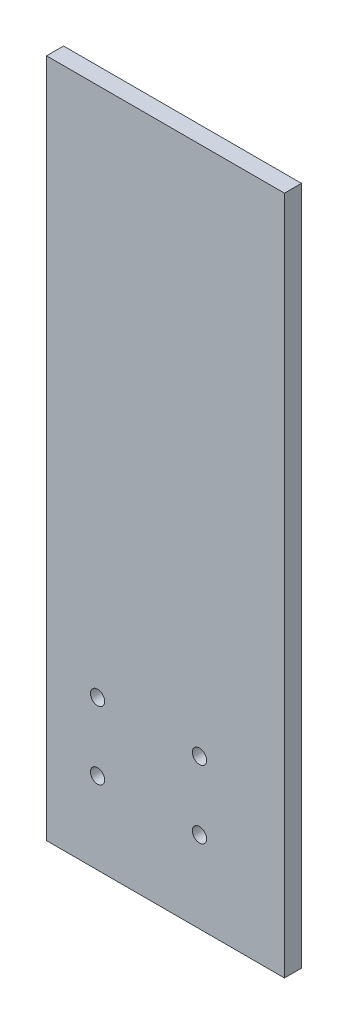
SolidWorks part; units mm, degrees
ref_plane "정면" through (0, 0, 0) normal (0, 0, 1) x (1, 0, 0)
ref_plane "윗면" through (0, 0, 0) normal (0, 1, 0) x (1, 0, 0)
ref_plane "우측면" through (0, 0, 0) normal (1, 0, 0) x (0, 0, -1)
sketch "스케치1" plane through (0, 0, 0) normal (0, 0, 1) x (1, 0, 0)
  line L1 (-50, 100) -> (50, 100)
  line L2 (-50, 100) -> (-50, -100)
  line L3 (-50, -100) -> (50, -100)
  line L4 (50, 100) -> (50, -100)
  line L5 (-50, 100) -> (50, -100) construction
  line L6 (-50, -100) -> (50, 100) construction
  point P0 (0, 0)
  dimension "D1" = 100
  dimension "D2" = 200
extrude "보스-돌출1" add sketch "스케치1" along normal blind 5
sketch "스케치3" plane through (0, 0, 0) normal (0, 0, -1) x (-1, 0, 0)
  text T0 "front"
extrude "컷-돌출2" cut sketch "스케치3" against normal blind 0.001
ref_plane "평면1" through (0, 0, -5) normal (0, 0, -1) x (-1, 0, 0)
hole_wizard "M4x0.7 Helicoil용 탭 구멍1" positions "스케치10" profile "스케치11" tap size "M4x0.7" standard "Helicoil® Metric" end condition through all
sketch "스케치10" plane through (0, 0, -5) normal (0, 0, -1) x (-1, 0, 0)
  line L0 (50, -100) -> (-50, -100) construction
  line L1 (-50, -100) -> (-50, 100) construction
  line L2 (50, 100) -> (50, -100) construction
  point P0 (-5, -76)
  point P2 (25, -76)
  point P4 (-5, -56)
  point P6 (25, -56)
  dimension "D1" = 24
  dimension "D2" = 24
  dimension "D3" = 45
  dimension "D4" = 25
  dimension "D5" = 25
  dimension "D6" = 45
  dimension "D7" = 20
  dimension "D8" = 20
sketch "스케치11" plane through (5, -76, -5) normal (1, 0, 0) x (0, 1, 0)
  line L0 (0, 0) -> (0, 10)
  line L1 (0, 10) -> (2.1, 10)
  line L2 (2.1, 10) -> (2.1, 0)
  line L5 (2.1, 0) -> (0, 0)
  line L11 (0, -6.35) -> (0, 107.95) construction
  dimension "관통 탭 드릴 지름" = 4.2
  dimension "관통 탭 드릴 깊이" = 10
cosmetic thread "구멍 나사산1" parameters "D1"=4.7, "D2"=5.007
cosmetic thread "구멍 나사산2" parameters "D1"=4.7, "D2"=5.007
cosmetic thread "구멍 나사산3" parameters "D1"=4.7, "D2"=5.007
cosmetic thread "구멍 나사산4" parameters "D1"=4.7, "D2"=5.007
sketch "스케치13" plane through (0, 0, 5) normal (0, 0, 1) x (1, 0, 0)
  line L0 (-50, -100) -> (50, -100) construction
  line L1 (50, 100) -> (40, 100)
  line L2 (50, 100) -> (50, -100)
  line L3 (50, -100) -> (40, -100)
  line L4 (40, 100) -> (40, -100)
  line L5 (0, -2.75) -> (0, 2.75) construction
  line L6 (-40, 100) -> (-40, -100)
  line L7 (-50, -100) -> (-40, -100)
  line L8 (-50, 100) -> (-50, -100)
  line L9 (-50, 100) -> (-40, 100)
  dimension "D1" = 10
extrude "컷-돌출4" cut sketch "스케치13" against normal blind 10
sketch "스케치14" plane through (0, 0, 5) normal (0, 0, 1) x (1, 0, 0)
  line L0 (-40, -100) -> (40, -100) construction
  line L1 (40, 100) -> (30, 100)
  line L2 (40, 100) -> (40, -100)
  line L3 (40, -100) -> (30, -100)
  line L4 (30, 100) -> (30, -100)
  dimension "D1" = 10
extrude "컷-돌출5" cut sketch "스케치14" against normal blind 10
